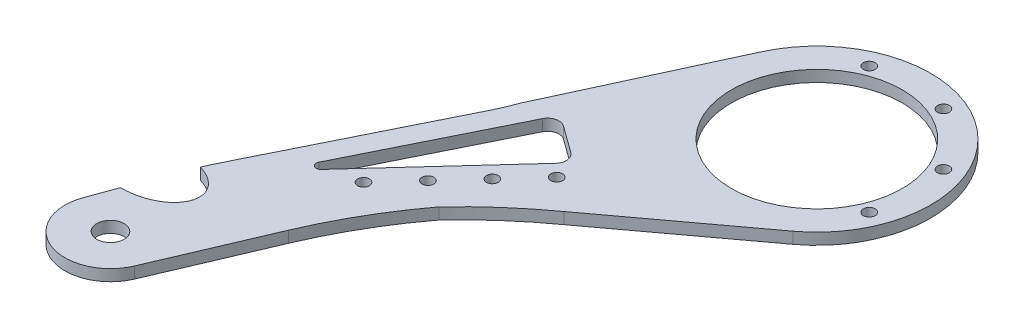
SolidWorks part; units mm, degrees
ref_plane "前视基准面" through (0, 0, 0) normal (0, 0, 1) x (1, 0, 0)
ref_plane "上视基准面" through (0, 0, 0) normal (0, 1, 0) x (1, 0, 0)
ref_plane "右视基准面" through (0, 0, 0) normal (1, 0, 0) x (0, 0, -1)
other "Configuration Table"
sketch "草图4" plane through (0, 0, 0) normal (0, 1, 0) x (1, 0, 0)
  line L8 (-23.7609, 24.4445) -> (-56.2498, -41.163)
  line L9 (-4.6476, 17.792) -> (-16.3452, 26.2736)
  line L10 (-52.9804, -43.399) -> (-3.89, 10.373)
  line L11 (-1.1871, 97.7564) -> (-34.4, 25.662)
  line L12 (-38.7551, 15.487) -> (-76.7022, -61.1428)
  line L13 (-90.0809, -94.3187) -> (-94.4471, -106.3148)
  line L14 (-57.2523, -120.9913) -> (-37.0735, -73.6073)
  line L15 (16.2792, -6.1001) -> (73.992, 36.6612)
  circle A28 centre (-75.6532, -113.1552) radius 6
  arc A35 (-56.2498, -41.163) -> (-52.9804, -43.399) centre (-54.4575, -42.0505) ccw
  arc A36 (-16.3452, 26.2736) -> (-23.7609, 24.4445) centre (-19.2802, 22.2256) ccw
  arc A37 (-3.89, 10.373) -> (-4.6476, 17.792) centre (-7.5826, 13.7441) ccw
  circle A38 centre (44.2256, 76.8354) radius 37.5
  circle A39 centre (-38.8047, -38.9952) radius 2.6
  circle A40 centre (-11.8356, -9.4542) radius 2.6
  circle A41 centre (-25.3201, -24.2247) radius 2.6
  circle A42 centre (1.649, 5.3163) radius 2.6
  arc A43 (-38.7551, 15.487) -> (-34.4, 25.662) centre (-128.3692, 59.864) ccw
  arc A44 (-76.7022, -61.1428) -> (-80.3755, -68.9828) centre (102.526, -149.8966) ccw
  arc A45 (-94.4471, -106.3148) -> (-57.2523, -120.9913) centre (-75.6532, -113.1552) ccw
  arc A46 (-12.9471, -31.8131) -> (-37.0735, -73.6073) centre (146.9359, -151.969) ccw
  arc A47 (16.2792, -6.1001) -> (-12.9471, -31.8131) centre (133.1467, -168.4023) ccw
  arc A48 (73.992, 36.6612) -> (-1.1871, 97.7564) centre (44.2256, 76.8354) ccw
  ellipse E0 centre (-88.7927, -81.1322) end of major axis (-108.39, -82.1835) minor radius 13.1666 (-90.0809, -94.3187) -> (-80.3755, -68.9828) ccw
extrude "凸台-拉伸1" add sketch "草图4" along normal blind 5
sketch "草图5" plane through (0, 5, 0) normal (0, 1, 0) x (1, 0, 0)
  line L0 (44.2256, 76.8354) -> (44.2256, 126.8354)
  line L1 (44.2256, 76.8354) -> (63.3598, 123.0294)
  circle A0 centre (44.2256, 76.8354) radius 37.5 construction
  circle A1 centre (44.2256, 76.8354) radius 37.5
  arc A2 (73.992, 36.6612) -> (-1.1871, 97.7564) centre (44.2256, 76.8354) ccw construction
  circle A3 centre (44.2256, 76.8354) radius 42.5
  circle A4 centre (60.4897, 116.1003) radius 2.6
  circle A5 centre (83.4905, 93.0994) radius 2.6
  circle A6 centre (83.4905, 60.5713) radius 2.6
  circle A7 centre (60.4897, 37.5705) radius 2.6
  circle A8 centre (27.9616, 37.5705) radius 2.6
  circle A9 centre (4.9607, 60.5713) radius 2.6
  circle A10 centre (4.9607, 93.0994) radius 2.6
  circle A11 centre (27.9616, 116.1003) radius 2.6
  point P13 (44.2256, 76.8354)
  point P28 (44.2256, 76.8354)
  dimension "D2" = 85
  dimension "D3" = 5.2
  dimension "D1" = 22.5
  dimension "D4" = 8
extrude "切除-拉伸1" cut sketch "草图5" against normal blind 5 contours L1 A4 A3 | L1 A4 A3 | A3 A4 L1 | A3 A4 L1 | A3 A11 | A3 A11 | A3 A6 | A3 A6 | A5
